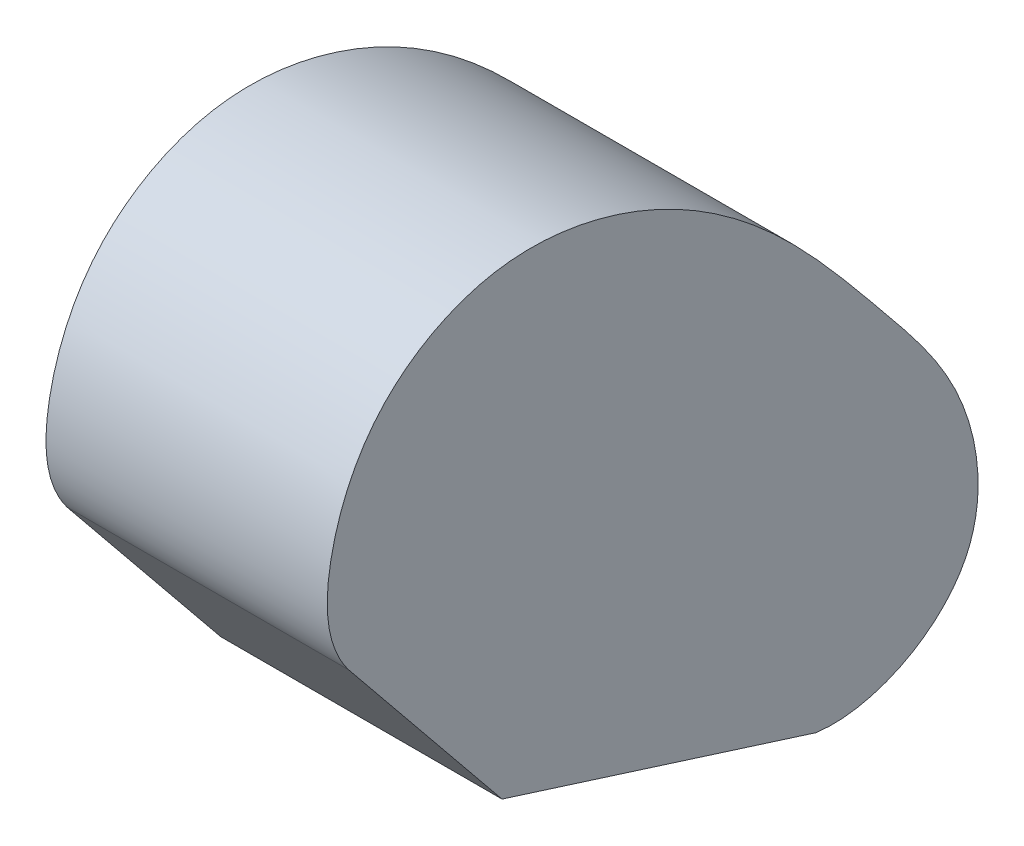
SolidWorks part; units mm, degrees
ref_plane "Front Plane" through (0, 0, 0) normal (0, 0, 1) x (1, 0, 0)
ref_plane "Top Plane" through (0, 0, 0) normal (0, 1, 0) x (1, 0, 0)
ref_plane "Right Plane" through (0, 0, 0) normal (1, 0, 0) x (0, 0, -1)
sketch "Sketch3" plane through (0, 0, 0) normal (1, 0, 0) x (0, 0, -1)
  line L0 (-53.3852, 70.0571) -> (10.0083, 23.3531) construction
  line L1 (-40.9761, 27.94) -> (-5.542, 16.714)
  line L2 (-40.9761, 27.94) -> (-58.3125, 49.2644)
  spline S0 degree 3 poles (-58.3125, 49.2644) (-60.9795, 52.8133) (-61.1644, 61.6455) (-55.5377, 74.0344) (-42.1637, 81.506) (-26.0626, 79.1513) (-10.3519, 69.3524) (1.1044, 55.1682) (12.2006, 41.6896) (14.4147, 22.4497) (0.9387, 15.8258) (-5.542, 16.714) knots 0 0 0 0 0.085904 0.177468 0.269425 0.38307 0.497612 0.648285 0.759107 0.861226 1 1 1 1
  dimension "D1" = 78.74
extrude "Boss-Extrude3" add sketch "Sketch3" against normal blind 31.75
sketch "Sketch4" plane through (-31.75, 0, 0) normal (-1, 0, 0) x (0, 0, 1)
  line L0 (2.4327, 67.0909) -> (57.6418, 26.4072) construction
  line L1 (51.6195, 47.8384) -> (38.9917, 30.5898)
  line L2 (38.9917, 30.5898) -> (12.8235, 30.5898)
  line L3 (12.8235, 63.4108) -> (12.8235, 30.5898)
  spline S0 degree 3 poles (12.8235, 63.4108) (16.0755, 66.3057) (21.7664, 70.0986) (31.2475, 74.5633) (41.3547, 74.4907) (53.4271, 66.0183) (54.3504, 53.9482) (51.6195, 47.8384) knots 0.403518 0.403518 0.403518 0.403518 0.529248 0.602051 0.703207 0.805208 1 1 1 1
  dimension "D1" = 68.58
extrude "Cut-Extrude1" cut sketch "Sketch4" against normal blind 26.67
